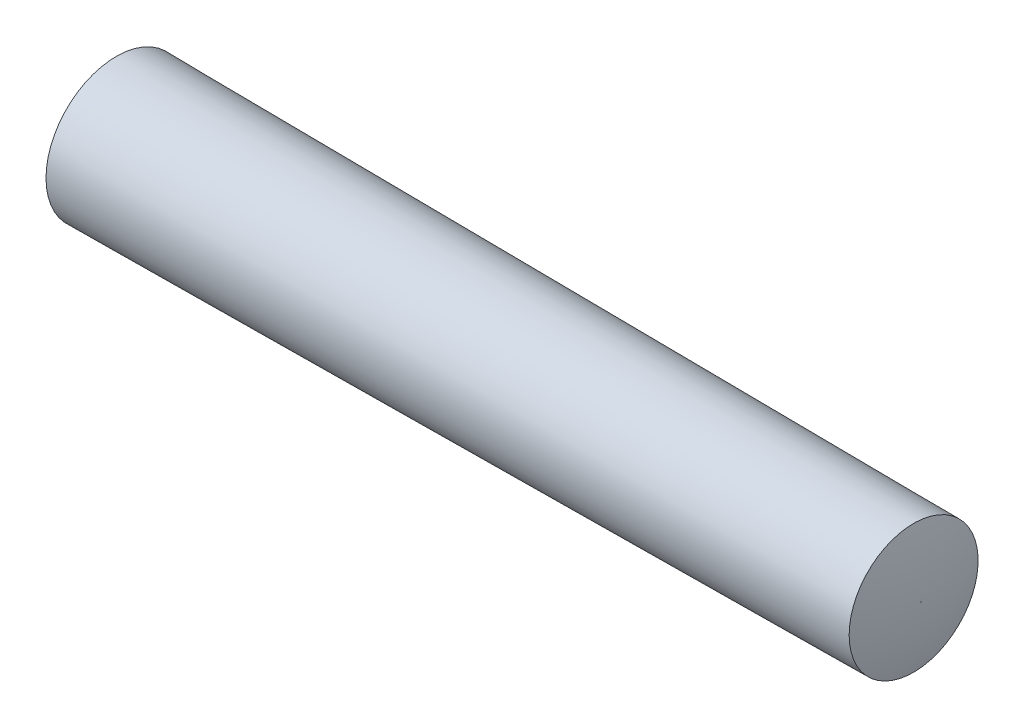
SolidWorks part; units mm, degrees
ref_plane "Plane1" through (0, 0, 0) normal (0, 0, 1) x (1, 0, 0)
ref_plane "Plane2" through (0, 0, 0) normal (0, 1, 0) x (1, 0, 0)
ref_plane "Plane3" through (0, 0, 0) normal (1, 0, 0) x (0, 0, -1)
sketch "Sketch1" plane through (0, 0, 0) normal (0, 0, 1) x (1, 0, 0)
  line L1 (-5.588, 0) -> (131.826, 0) construction
  line L2 (0, 0) -> (0, 0.0897)
  line L3 (0, 0) -> (103.6493, 0)
  line L4 (103.6493, 0) -> (103.6493, 0.0897)
  line L5 (102.7158, 8.219) -> (1.1158, 8.9662)
  arc A0 (0, 0.0897) -> (1.1158, 8.9662) centre (35.8648, 0.0897) cw
  arc A1 (103.6493, 0.0897) -> (102.7158, 8.219) centre (67.7845, 0.0897) ccw
  dimension "D3" = 35.8648
  dimension "D4" = 35.8648
  dimension "D1" = 0.0897
  dimension "D2" = 0.0897
  dimension "Length" = 101.6
  dimension "Diameter" = 17.9324
  dimension "D5" = 16.438
revolve "Base-Revolve" add sketch "Sketch1" angle 360 about L1
equation "\"D1@Sketch1\" = \"Diameter@Sketch1\" / 100 / 2"
equation "\"D2@Sketch1\" = \"Diameter@Sketch1\" / 100 / 2"
equation "\"D3@Sketch1\" = \"Diameter@Sketch1\" *2"
equation "\"D4@Sketch1\" = \"Diameter@Sketch1\" *2"
equation "\"D5@Sketch1\" = \"Diameter@Sketch1\" -  (\"Length@Sketch1\" * (1/48) * \"Diameter@Sketch1\")"
